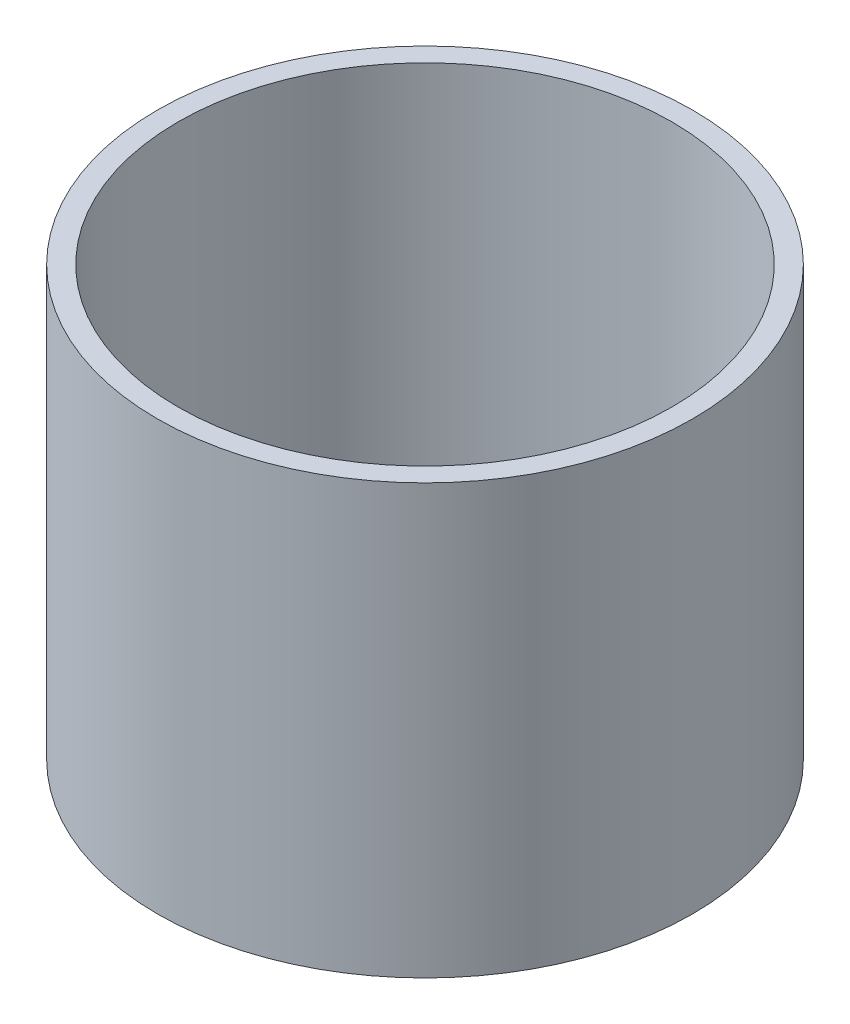
SolidWorks part; units mm, degrees
ref_plane "Front Plane" through (0, 0, 0) normal (0, 0, 1) x (1, 0, 0)
ref_plane "Top Plane" through (0, 0, 0) normal (0, 1, 0) x (1, 0, 0)
ref_plane "Right Plane" through (0, 0, 0) normal (1, 0, 0) x (0, 0, -1)
sketch "Sketch1" plane through (0, 0, 0) normal (0, 1, 0) x (1, 0, 0)
  circle A1 centre (0, 0) radius 15.6
  dimension "D2" = 31.2
extrude "Boss-Extrude1" add sketch "Sketch1" against normal blind 3
sketch "Sketch2" plane through (0, 0, 0) normal (0, 1, 0) x (1, 0, 0)
  circle A0 centre (0, 0) radius 4.275
  dimension "D1" = 8.55
extrude "Cut-Extrude1" cut sketch "Sketch2" against normal blind 1.5
sketch "Sketch3" plane through (0, 0, 0) normal (0, 1, 0) x (1, 0, 0)
  circle A0 centre (0, 0) radius 14.4
  circle A1 centre (0, 0) radius 15.6
  dimension "D1" = 28.8
  dimension "D2" = 31.2
extrude "Boss-Extrude2" add sketch "Sketch3" along normal blind 22
sketch "Sketch4" plane through (0, -3, 0) normal (0, -1, 0) x (-1, 0, 0)
  line L0 (-1.6395, -2.5124) -> (3.2789, 5.0248) construction
  line L1 (-5.9911, 0.3272) -> (2.7121, -5.352)
  line L2 (2.7121, -5.352) -> (3.2789, 5.0248)
  line L3 (3.2789, 5.0248) -> (-5.9911, 0.3272)
  line L4 (-1.3561, 2.676) -> (2.7121, -5.352) construction
  circle A0 centre (0, 0) radius 6 construction
  circle A1 centre (-5.9911, 0.3272) radius 1
  circle A2 centre (3.2789, 5.0248) radius 1
  circle A3 centre (2.7121, -5.352) radius 1
  dimension "D1" = 12
  dimension "D2" = 2
  dimension "D3" = 9.27
extrude "Cut-Extrude3" cut sketch "Sketch4" against normal blind 3 contours A1 | A2 | A3
